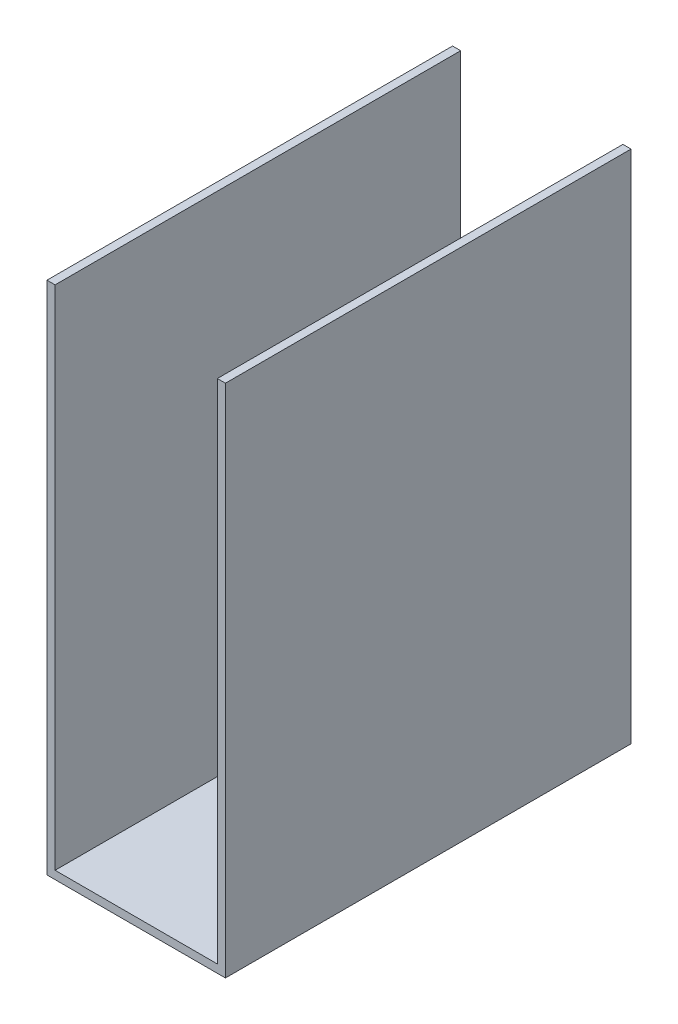
SolidWorks part; units mm, degrees
ref_plane "Front Plane" through (0, 0, 0) normal (0, 0, 1) x (1, 0, 0)
ref_plane "Top Plane" through (0, 0, 0) normal (0, 1, 0) x (1, 0, 0)
ref_plane "Right Plane" through (0, 0, 0) normal (1, 0, 0) x (0, 0, -1)
sketch "Sketch2" plane through (0, 0, 0) normal (0, 0, 1) x (1, 0, 0)
  line L0 (0, 0) -> (0, -12500)
  line L1 (0, -12500) -> (4000, -12500)
  line L2 (4000, -12500) -> (4000, 0)
  line L3 (-200, 0) -> (-200, -12700)
  line L4 (-200, -12700) -> (4200, -12700)
  line L5 (4200, -12700) -> (4200, 0)
  line L6 (-200, 0) -> (0, 0)
  line L7 (4000, 0) -> (4200, 0)
extrude "Boss-Extrude1" add sketch "Sketch2" against normal blind 10000
